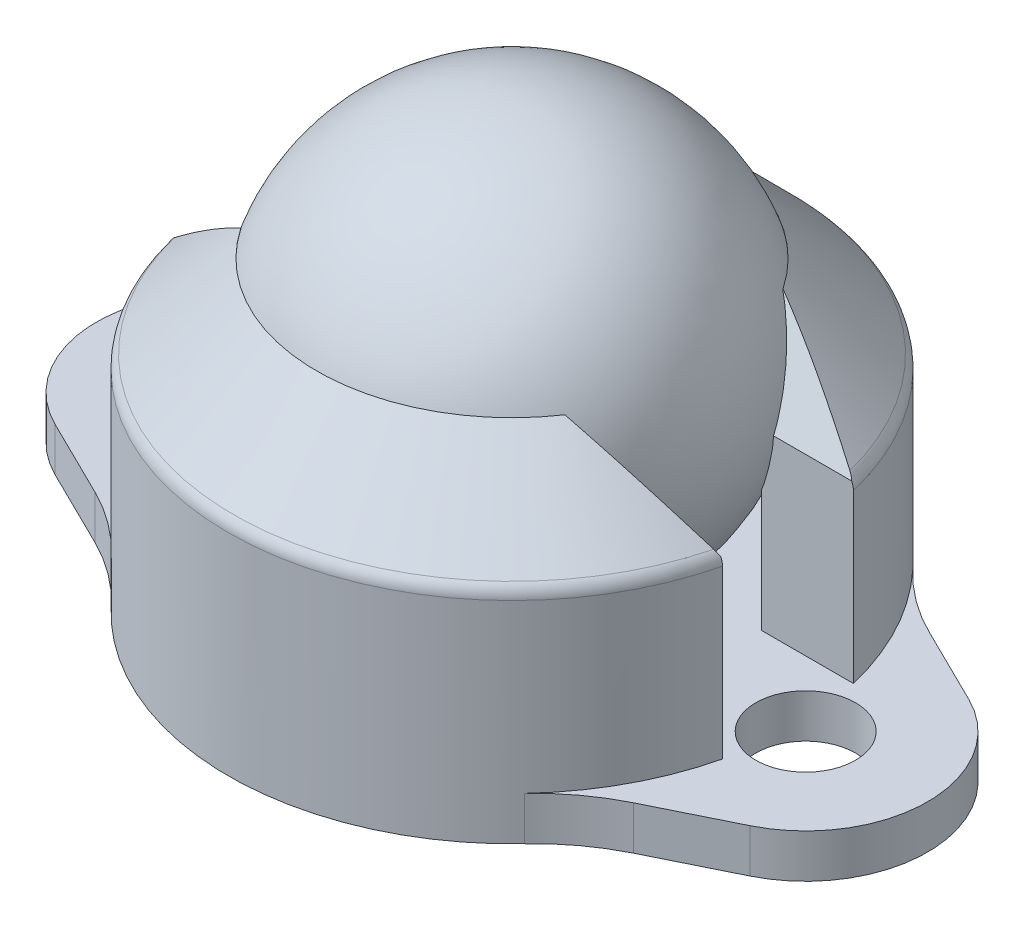
SolidWorks part; units mm, degrees
ref_plane "Přední rovina" through (0, 0, 0) normal (0, 0, 1) x (1, 0, 0)
ref_plane "Horní rovina" through (0, 0, 0) normal (0, 1, 0) x (1, 0, 0)
ref_plane "Pravá rovina" through (0, 0, 0) normal (1, 0, 0) x (0, 0, -1)
sketch "Skica1" plane through (0, 0, 0) normal (0, 1, 0) x (1, 0, 0)
  line L0 (9.525, 0) -> (-9.525, 0) construction
  line L1 (0, 0) -> (0, 5.7859) construction
  line L2 (-7.9653, 2.5066) -> (-6.171, 3.3901)
  line L3 (-7.9653, -2.5066) -> (-6.171, -3.3901)
  line L4 (7.9653, -2.5066) -> (6.171, -3.3901)
  line L5 (7.9653, 2.5066) -> (6.171, 3.3901)
  arc A0 (6.171, -3.3901) -> (4.7365, -4.4515) centre (8.3799, -7.8758) ccw
  circle A1 centre (-6.731, 0) radius 1.143
  arc A2 (-7.9653, 2.5066) -> (-7.9653, -2.5066) centre (-6.731, 0) ccw
  arc A3 (-6.171, 3.3901) -> (-4.7365, 4.4515) centre (-8.3799, 7.8758) ccw
  arc A4 (-6.171, -3.3901) -> (-4.7365, -4.4515) centre (-8.3799, -7.8758) cw
  arc A5 (-4.7365, -4.4515) -> (4.7365, -4.4515) centre (0, 0) ccw
  circle A6 centre (6.731, 0) radius 1.143
  arc A7 (7.9653, 2.5066) -> (7.9653, -2.5066) centre (6.731, 0) cw
  arc A8 (6.171, 3.3901) -> (4.7365, 4.4515) centre (8.3799, 7.8758) cw
  arc A9 (4.7365, 4.4515) -> (-4.7365, 4.4515) centre (0, 0) ccw
  dimension "D1" = 19.05
  dimension "D2" = 2.286
  dimension "D3" = 13.462
  dimension "D4" = 6.5
  dimension "D5" = 5
  dimension "D6" = 2
extrude "Přidat vysunutím1" add sketch "Skica1" along normal blind 1
sketch "Skica2" plane through (0, 0, 0) normal (0, 0, 1) x (1, 0, 0)
  line L0 (-4.7365, 0) -> (4.7365, 0) construction
  line L1 (0, 0) -> (0, 14.4673) construction
  line L2 (0, 10.16) -> (0, 0.635)
  arc A0 (0, 0.635) -> (0, 10.16) centre (0, 5.3975) ccw
  dimension "D1" = 10.16
  dimension "D2" = 9.525
revolve "Rotovat2" add sketch "Skica2" angle 360 about L1
sketch "Skica3" plane through (0, 0, 0) normal (1, 0, 0) x (0, 0, -1)
  line L0 (6.5, 1) -> (6.5, 4.8288)
  line L1 (6.3778, 5.1239) -> (4.4753, 7.0264)
  line L2 (4.4753, 7.0264) -> (4.4753, 1)
  line L3 (0, 5.3975) -> (4.4753, 7.0264) construction
  line L4 (6.5, 1) -> (4.4515, 1) construction
  line L5 (4.4753, 7.0264) -> (2.9657, 4.7297) construction
  line L6 (4.4753, 1) -> (6.5, 1)
  line L7 (0, 5.3975) -> (2.9093, 5.3975) construction
  line L8 (6.5, 4.8288) -> (0, 5.3975) construction
  line L9 (0, 0) -> (0, 9.3673) construction
  circle A0 centre (0, 5.3975) radius 4.7625 construction
  arc A1 (6.5, 4.8288) -> (6.3778, 5.1239) centre (6.0827, 4.8288) ccw
  circle A2 centre (0, 5.3975) radius 4.7625 construction
  point P9 (6.5, 5.0017)
  dimension "D3" = 45
  dimension "D1" = 20
  dimension "D2" = 5
revolve "Rotovat5" add sketch "Skica3" angle 360 about L9
sketch "Skica4" plane through (0, 0, 0) normal (1, 0, 0) x (0, 0, -1)
  line L0 (-2.5, 7.0264) -> (-1.5, 5)
  line L2 (-1.5, 5) -> (-1.5, 1)
  line L3 (-1.0961, 1) -> (-4.4515, 1) construction
  line L4 (0, 0) -> (0, 10.4938) construction
  line L5 (1.5, 5) -> (1.5, 1)
  line L6 (2.5, 7.0264) -> (1.5, 5)
  line L7 (-2.5, 7.0264) -> (2.5, 7.0264)
  line L8 (-1.5, 1) -> (1.5, 1)
  line L9 (1.5, 1) -> (1.4592, 2.0553)
  line L10 (4.4753, 7.0264) -> (-4.4753, 7.0264) construction
  dimension "D1" = 3
  dimension "D2" = 5
  dimension "D3" = 4
extrude "Odebrat vysunutím1" cut sketch "Skica4" against normal through all and the other way through all contours L5 L6 L7 L0 L2 L8
